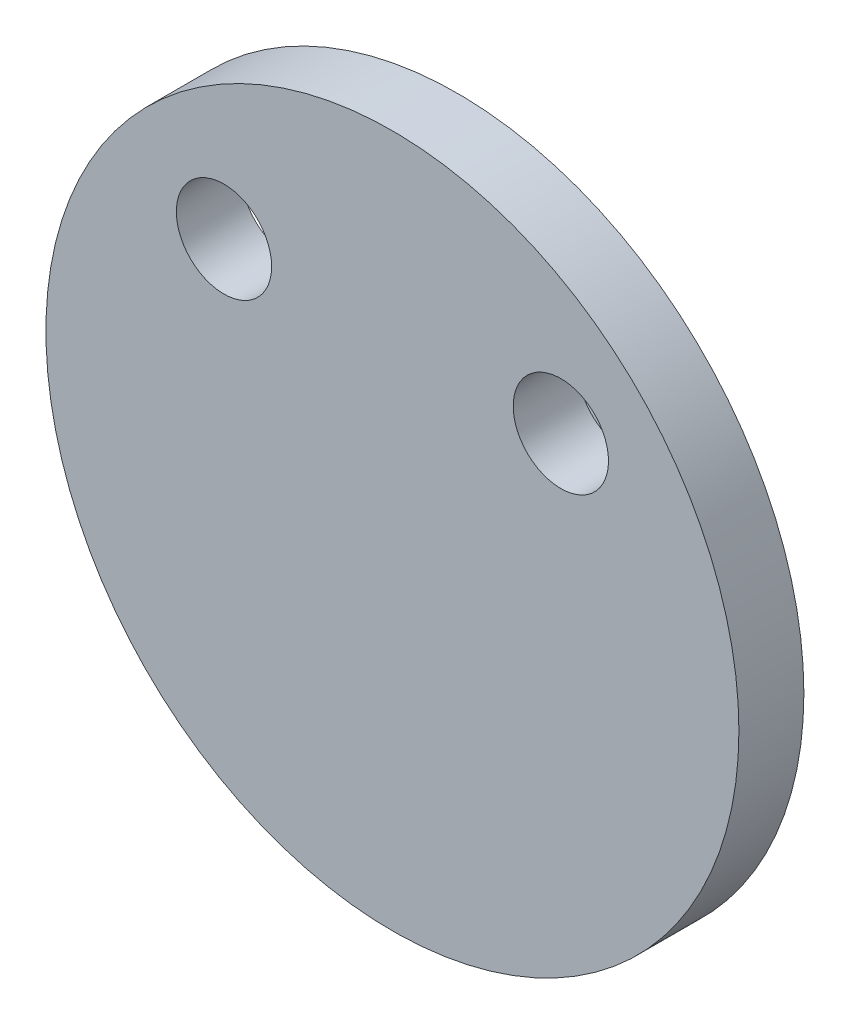
SolidWorks part; units mm, degrees
material "Nylon 6/10"
ref_plane "Plan de face" through (0, 0, 0) normal (0, 0, 1) x (1, 0, 0)
ref_plane "Plan de dessus" through (0, 0, 0) normal (0, 1, 0) x (1, 0, 0)
ref_plane "Plan de droite" through (0, 0, 0) normal (1, 0, 0) x (0, 0, -1)
sketch "Esquisse1" plane through (0, 0, 0) normal (0, 0, 1) x (1, 0, 0)
  circle A0 centre (0, 0) radius 8
  circle A1 centre (3.8891, 3.8891) radius 1.1
  circle A2 centre (-3.8891, 3.8891) radius 1.1
extrude "Disque O16" add sketch "Esquisse1" along normal blind 1.5
sketch "Esquisse2" plane through (0, 0, 0) normal (0, 0, 1) x (1, 0, 0)
  circle A0 centre (0, 0) radius 3.5
  circle A1 centre (0, 0) radius 2.35
extrude "Moyeu cannele SG90" add sketch "Esquisse2" against normal blind 3
